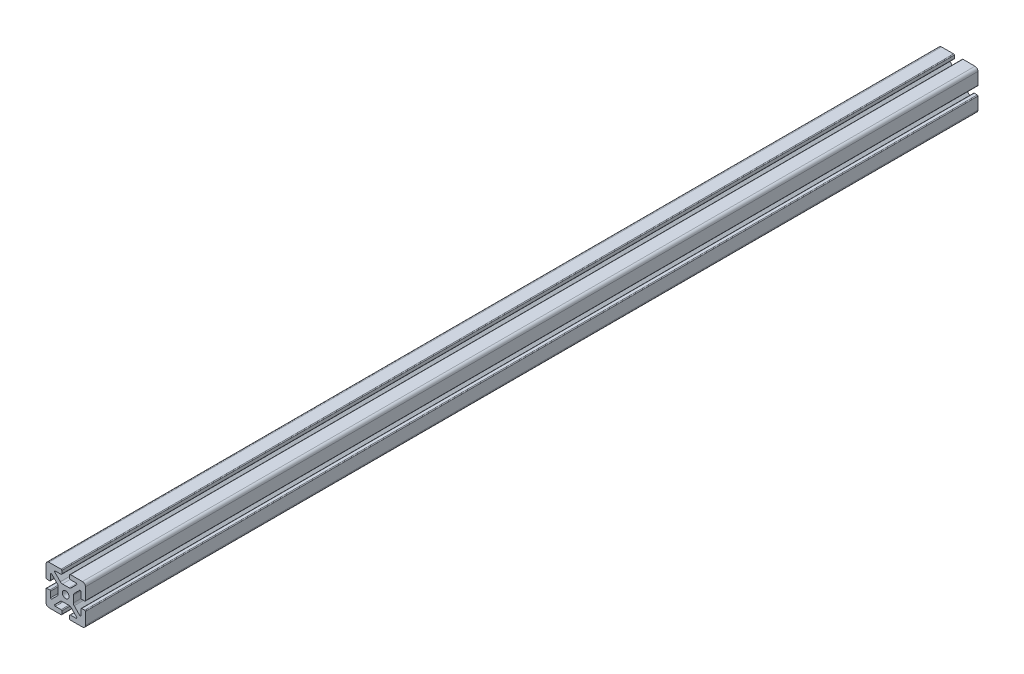
SolidWorks part; units mm, degrees
ref_plane "Front Plane" through (0, 0, 0) normal (0, 0, 1) x (1, 0, 0)
ref_plane "Top Plane" through (0, 0, 0) normal (0, 1, 0) x (1, 0, 0)
ref_plane "Right Plane" through (0, 0, 0) normal (1, 0, 0) x (0, 0, -1)
sketch "Sketch1" plane through (0, 0, 0) normal (0, 0, 1) x (1, 0, 0)
  line L0 (0, 20) -> (0, -20) construction
  line L1 (-20, 0) -> (20, 0) construction
  line L2 (-20, 16.952) -> (-20, 4.7625)
  line L3 (-16.952, 20) -> (-4.7625, 20)
  line L4 (-4.0005, 19.238) -> (-4.0005, 16.2662)
  line L5 (-4.7625, 15.5042) -> (-10.4856, 15.5042)
  line L6 (-11.0244, 14.2034) -> (-5.456, 8.6351)
  line L7 (-14.2034, 11.0244) -> (-8.6351, 5.456)
  line L8 (-15.5042, 10.4856) -> (-15.5042, 4.7625)
  line L9 (-16.2662, 4.0005) -> (-19.238, 4.0005)
  line L10 (0, 0) -> (-20, 20) construction
  line L11 (-3.3367, 7.7572) -> (3.3367, 7.7572)
  line L12 (-7.7572, 3.3367) -> (-7.7572, -3.3367)
  line L13 (16.2662, 4.0005) -> (19.238, 4.0005)
  line L14 (15.5042, 10.4856) -> (15.5042, 4.7625)
  line L15 (20, 16.952) -> (20, 4.7625)
  line L16 (16.952, 20) -> (4.7625, 20)
  line L17 (4.0005, 19.238) -> (4.0005, 16.2662)
  line L18 (4.7625, 15.5042) -> (10.4856, 15.5042)
  line L19 (7.7572, 3.3367) -> (7.7572, -3.3367)
  line L20 (11.0244, 14.2034) -> (5.456, 8.6351)
  line L21 (14.2034, 11.0244) -> (8.6351, 5.456)
  line L22 (-16.2662, -4.0005) -> (-19.238, -4.0005)
  line L23 (-15.5042, -10.4856) -> (-15.5042, -4.7625)
  line L24 (-14.2034, -11.0244) -> (-8.6351, -5.456)
  line L25 (-11.0244, -14.2034) -> (-5.456, -8.6351)
  line L26 (-4.7625, -15.5042) -> (-10.4856, -15.5042)
  line L27 (-4.0005, -19.238) -> (-4.0005, -16.2662)
  line L28 (-16.952, -20) -> (-4.7625, -20)
  line L29 (-20, -16.952) -> (-20, -4.7625)
  line L30 (20, -16.952) -> (20, -4.7625)
  line L31 (16.952, -20) -> (4.7625, -20)
  line L32 (4.0005, -19.238) -> (4.0005, -16.2662)
  line L33 (4.7625, -15.5042) -> (10.4856, -15.5042)
  line L34 (11.0244, -14.2034) -> (5.456, -8.6351)
  line L35 (14.2034, -11.0244) -> (8.6351, -5.456)
  line L36 (15.5042, -10.4856) -> (15.5042, -4.7625)
  line L37 (16.2662, -4.0005) -> (19.238, -4.0005)
  line L38 (-3.3367, -7.7572) -> (3.3367, -7.7572)
  circle A0 centre (0, 0) radius 3.4036
  arc A1 (-20, 16.952) -> (-16.952, 20) centre (-16.952, 16.952) cw
  arc A2 (-14.2034, 11.0244) -> (-15.5042, 10.4856) centre (-14.7422, 10.4856) ccw
  arc A3 (-10.4856, 15.5042) -> (-11.0244, 14.2034) centre (-10.4856, 14.7422) ccw
  arc A4 (-4.7625, 20) -> (-4.0005, 19.238) centre (-4.7625, 19.238) cw
  arc A5 (-20, 4.7625) -> (-19.238, 4.0005) centre (-19.238, 4.7625) ccw
  arc A6 (-15.5042, 4.7625) -> (-16.2662, 4.0005) centre (-16.2662, 4.7625) cw
  arc A7 (-4.0005, 16.2662) -> (-4.7625, 15.5042) centre (-4.7625, 16.2662) cw
  arc A8 (-3.3367, 7.7572) -> (-5.456, 8.6351) centre (-3.3367, 10.7544) cw
  arc A9 (-7.7572, 3.3367) -> (-8.6351, 5.456) centre (-10.7544, 3.3367) ccw
  arc A10 (15.5042, 4.7625) -> (16.2662, 4.0005) centre (16.2662, 4.7625) ccw
  arc A11 (20, 4.7625) -> (19.238, 4.0005) centre (19.238, 4.7625) cw
  arc A12 (20, 16.952) -> (16.952, 20) centre (16.952, 16.952) ccw
  arc A13 (4.7625, 20) -> (4.0005, 19.238) centre (4.7625, 19.238) ccw
  arc A14 (4.0005, 16.2662) -> (4.7625, 15.5042) centre (4.7625, 16.2662) ccw
  arc A15 (3.3367, 7.7572) -> (5.456, 8.6351) centre (3.3367, 10.7544) ccw
  arc A16 (7.7572, 3.3367) -> (8.6351, 5.456) centre (10.7544, 3.3367) cw
  arc A17 (14.2034, 11.0244) -> (15.5042, 10.4856) centre (14.7422, 10.4856) cw
  arc A18 (10.4856, 15.5042) -> (11.0244, 14.2034) centre (10.4856, 14.7422) cw
  arc A19 (-7.7572, -3.3367) -> (-8.6351, -5.456) centre (-10.7544, -3.3367) cw
  arc A20 (-3.3367, -7.7572) -> (-5.456, -8.6351) centre (-3.3367, -10.7544) ccw
  arc A21 (-4.0005, -16.2662) -> (-4.7625, -15.5042) centre (-4.7625, -16.2662) ccw
  arc A22 (-15.5042, -4.7625) -> (-16.2662, -4.0005) centre (-16.2662, -4.7625) ccw
  arc A23 (-20, -4.7625) -> (-19.238, -4.0005) centre (-19.238, -4.7625) cw
  arc A24 (-4.7625, -20) -> (-4.0005, -19.238) centre (-4.7625, -19.238) ccw
  arc A25 (-10.4856, -15.5042) -> (-11.0244, -14.2034) centre (-10.4856, -14.7422) cw
  arc A26 (-14.2034, -11.0244) -> (-15.5042, -10.4856) centre (-14.7422, -10.4856) cw
  arc A27 (-20, -16.952) -> (-16.952, -20) centre (-16.952, -16.952) ccw
  arc A28 (20, -16.952) -> (16.952, -20) centre (16.952, -16.952) cw
  arc A29 (14.2034, -11.0244) -> (15.5042, -10.4856) centre (14.7422, -10.4856) ccw
  arc A30 (10.4856, -15.5042) -> (11.0244, -14.2034) centre (10.4856, -14.7422) ccw
  arc A31 (4.7625, -20) -> (4.0005, -19.238) centre (4.7625, -19.238) cw
  arc A32 (20, -4.7625) -> (19.238, -4.0005) centre (19.238, -4.7625) ccw
  arc A33 (15.5042, -4.7625) -> (16.2662, -4.0005) centre (16.2662, -4.7625) cw
  arc A34 (4.0005, -16.2662) -> (4.7625, -15.5042) centre (4.7625, -16.2662) cw
  arc A35 (3.3367, -7.7572) -> (5.456, -8.6351) centre (3.3367, -10.7544) cw
  arc A36 (7.7572, -3.3367) -> (8.6351, -5.456) centre (10.7544, -3.3367) ccw
  point P29 (-20, 4.0005)
  point P32 (-15.5042, 4.0005)
  point P36 (-4.5782, 7.7572)
  point P68 (0, 7.7572)
  dimension "D4" = 6.8072
  dimension "D5" = 3.048
  dimension "D6" = 0.762
  dimension "D9" = 0.762
  dimension "D10" = 0.762
  dimension "D11" = 4.4958
  dimension "D13" = 2.9972
  dimension "D1" = 40
  dimension "D2" = 40
  dimension "D3" = 12.2428
  dimension "D7" = 8.001
  dimension "D8" = 4.4958
extrude "Extrude1" add sketch "Sketch1" along normal mid plane 1270
ref_plane "Plane1" through (0, 16.952, 0) normal (0, 1, 0) x (1, 0, 0)
sketch "Sketch4" plane through (0, 16.952, 0) normal (0, 1, 0) x (1, 0, 0)
  line L0 (-23.4696, 270.5) -> (35.0321, 270.5)
  line L1 (-909, 270.5) -> (-20, 270.5) construction
  line L2 (35.0321, 270.5) -> (35.0321, 659.8832)
  line L3 (35.0321, 659.8832) -> (-23.4696, 659.8832)
  line L4 (-23.4696, 659.8832) -> (-23.4696, 270.5)
extrude "Cut-Extrude1" cut sketch "Sketch4" against normal up to surface (36.952 mm away) up to face at (10.8573, -20, 0)
sketch "Sketch5" plane through (0, 16.952, 0) normal (0, -1, 0) x (1, 0, 0)
  line L1 (20, -270.5) -> (-20, -270.5)
  line L2 (20, -270.5) -> (20, -635)
  line L3 (20, -635) -> (-20, -635)
  line L4 (-20, -270.5) -> (-20, -635)
extrude "Cut-Extrude2" cut sketch "Sketch5" against normal up to surface (3.048 mm away) up to face at (10.8573, 20, 0)
equation "\"D2@Sketch1\" = \"D1@Sketch1\""
